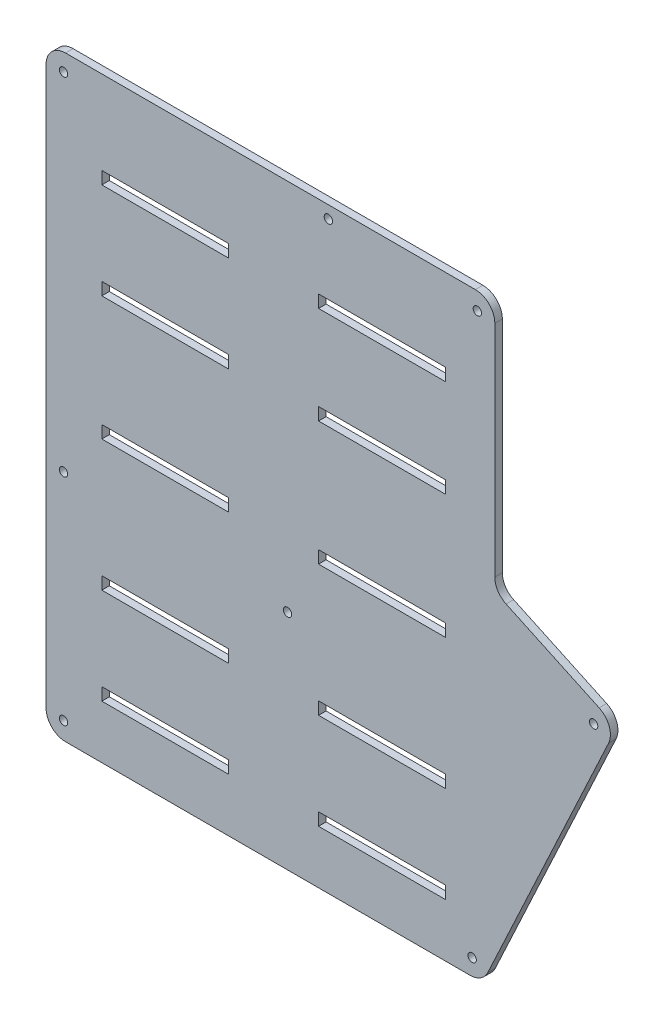
SolidWorks part; units mm, degrees
ref_plane "Front Plane" through (0, 0, 0) normal (0, 0, 1) x (1, 0, 0)
ref_plane "Top Plane" through (0, 0, 0) normal (0, 1, 0) x (1, 0, 0)
ref_plane "Right Plane" through (0, 0, 0) normal (1, 0, 0) x (0, 0, -1)
sketch "Sketch1" plane through (0, 0, 0) normal (0, 0, 1) x (1, 0, 0)
  line L0 (181.0868, 176.698) -> (181.0868, 97.8093)
  line L1 (27, 183.698) -> (174.0868, 183.698)
  line L2 (185.1287, 91.4651) -> (218.5389, 75.8869)
  line L3 (20, -23.4406) -> (20, 176.698)
  line L4 (172.2224, -30.4406) -> (27, -30.4406)
  line L5 (221.925, 66.5844) -> (178.5665, -26.3989)
  line L6 (117.8068, 154.198) -> (163.3692, 154.198)
  line L7 (40, 153.698) -> (85.5624, 153.698)
  line L8 (40, 153.698) -> (40, 149.198)
  line L9 (40, 149.198) -> (85.5624, 149.198)
  line L10 (85.5624, 153.698) -> (85.5624, 149.198)
  line L11 (40, 119.198) -> (85.5624, 119.198)
  line L12 (40, 119.198) -> (40, 114.698)
  line L13 (40, 114.698) -> (85.5624, 114.698)
  line L14 (85.5624, 119.198) -> (85.5624, 114.698)
  line L15 (40, 74.698) -> (85.5624, 74.698)
  line L16 (40, 74.698) -> (40, 70.198)
  line L17 (40, 70.198) -> (85.5624, 70.198)
  line L18 (85.5624, 74.698) -> (85.5624, 70.198)
  line L19 (40, 27.698) -> (85.5624, 27.698)
  line L20 (40, 27.698) -> (40, 23.198)
  line L21 (40, 23.198) -> (85.5624, 23.198)
  line L22 (85.5624, 27.698) -> (85.5624, 23.198)
  line L23 (40, -6.802) -> (85.5624, -6.802)
  line L24 (40, -6.802) -> (40, -11.302)
  line L25 (40, -11.302) -> (85.5624, -11.302)
  line L26 (85.5624, -6.802) -> (85.5624, -11.302)
  line L27 (117.8068, 154.198) -> (117.8068, 149.698)
  line L28 (117.8068, 149.698) -> (163.3692, 149.698)
  line L29 (163.3692, 154.198) -> (163.3692, 149.698)
  line L30 (117.8068, 119.198) -> (163.3692, 119.198)
  line L31 (117.8068, 119.198) -> (117.8068, 114.698)
  line L32 (117.8068, 114.698) -> (163.3692, 114.698)
  line L33 (163.3692, 119.198) -> (163.3692, 114.698)
  line L34 (117.8068, 74.698) -> (163.3692, 74.698)
  line L35 (117.8068, 74.698) -> (117.8068, 70.198)
  line L36 (117.8068, 70.198) -> (163.3692, 70.198)
  line L37 (163.3692, 74.698) -> (163.3692, 70.198)
  line L38 (117.8068, 27.698) -> (163.3692, 27.698)
  line L39 (117.8068, 27.698) -> (117.8068, 23.198)
  line L40 (117.8068, 23.198) -> (163.3692, 23.198)
  line L41 (163.3692, 27.698) -> (163.3692, 23.198)
  line L42 (117.8068, -6.802) -> (163.3692, -6.802)
  line L43 (117.8068, -6.802) -> (117.8068, -11.302)
  line L44 (117.8068, -11.302) -> (163.3692, -11.302)
  line L45 (163.3692, -6.802) -> (163.3692, -11.302)
  circle A0 centre (216.5585, 69.8985) radius 1.5
  circle A1 centre (106.6699, 49.713) radius 1.5
  circle A2 centre (26.2639, 53.1194) radius 1.5
  circle A3 centre (26.2639, 177.4341) radius 1.5
  circle A4 centre (121.3333, 179.253) radius 1.5
  circle A5 centre (174.8166, 177.4341) radius 1.5
  arc A6 (27, 183.698) -> (20, 176.698) centre (27, 176.698) ccw
  arc A7 (181.0868, 176.698) -> (174.0868, 183.698) centre (174.0868, 176.698) ccw
  arc A8 (221.925, 66.5844) -> (218.5389, 75.8869) centre (215.5808, 69.5427) ccw
  arc A9 (181.0868, 97.8093) -> (185.1287, 91.4651) centre (188.0868, 97.8093) ccw
  arc A12 (20, -23.4406) -> (27, -30.4406) centre (27, -23.4406) ccw
  arc A13 (172.2224, -30.4406) -> (178.5665, -26.3989) centre (172.2224, -23.4406) ccw
  circle A14 centre (26.2639, -24.1767) radius 1.5
  circle A15 centre (172.941, -24.5686) radius 1.5
  dimension "D3" = 3
  dimension "D1" = 161.0868
  dimension "D2" = 214.1386
  dimension "D4" = 4.5
  dimension "D5" = 20
  dimension "D6" = 42.5
  dimension "D7" = 30
  dimension "D8" = 30
  dimension "D9" = 40
  dimension "D11" = 30
extrude "Boss-Extrude1" add sketch "Sketch1" along normal blind 2.7
